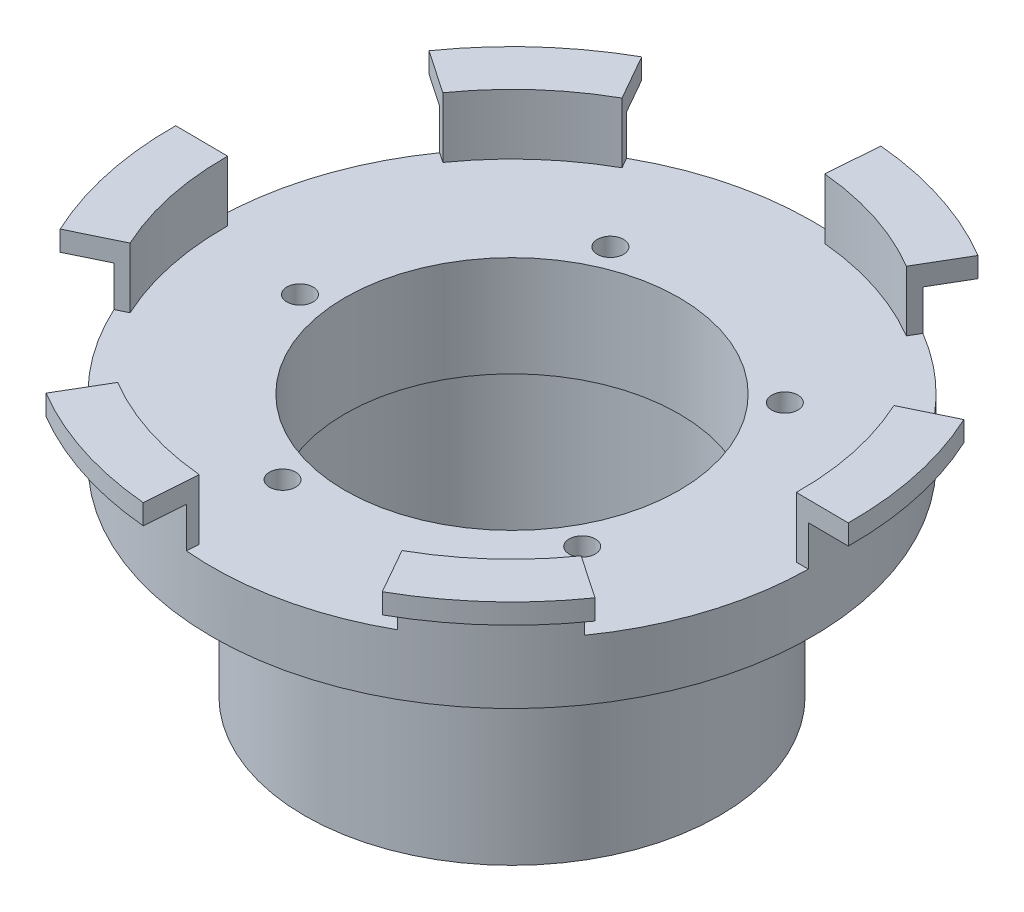
SolidWorks part; units mm, degrees
material "ABS PC"
ref_plane "Front Plane" through (0, 0, 0) normal (0, 0, 1) x (1, 0, 0)
ref_plane "Top Plane" through (0, 0, 0) normal (0, 1, 0) x (1, 0, 0)
ref_plane "Right Plane" through (0, 0, 0) normal (1, 0, 0) x (0, 0, -1)
sketch "Sketch1" plane through (0, 0, 0) normal (0, 1, 0) x (1, 0, 0)
  circle A0 centre (-1.3362, 19.9052) radius 41.5
  circle A1 centre (-1.3362, 19.9052) radius 71.5
  circle A2 centre (40.1859, -4.1762) radius 3.25
  circle A3 centre (34.3976, 51.9535) radius 3.25
  circle A4 centre (-20.7736, 63.7936) radius 3.25
  circle A5 centre (-49.083, 14.9815) radius 3.25
  circle A6 centre (-11.408, -27.0262) radius 3.25
  circle A7 centre (-1.3362, 19.9052) radius 41.5 construction
  dimension "D1" = 6.5
  dimension "D2" = 30
extrude "Boss-Extrude1" add sketch "Sketch1" along normal blind 15
sketch "Sketch3" plane through (0, 0, 0) normal (0, -1, 0) x (1, 0, 0)
  circle A0 centre (-1.3362, -19.9052) radius 71.5 construction
  circle A1 centre (-1.3362, -19.9052) radius 71.5
  circle A2 centre (-1.3362, -19.9052) radius 74.5
  dimension "D1" = 3
extrude "Boss-Extrude2" add sketch "Sketch3" against normal blind 30
sketch "Sketch4" plane through (0, 30, 0) normal (0, 1, 0) x (1, 0, 0)
  circle A0 centre (-1.3362, 19.9052) radius 74.5 construction
  circle A1 centre (-1.3362, 19.9052) radius 74.5
  circle A2 centre (-1.3362, 19.9052) radius 84.5
  dimension "D1" = 10
extrude "Boss-Extrude3" add sketch "Sketch4" against normal blind 5
sketch "Sketch5" plane through (0, 0, 0) normal (0, -1, 0) x (1, 0, 0)
  circle A0 centre (-1.3362, -19.9052) radius 41.5 construction
  circle A1 centre (-1.3362, -19.9052) radius 41.5
  circle A2 centre (-1.3362, -19.9052) radius 51.5
  dimension "D1" = 10
extrude "Boss-Extrude4" add sketch "Sketch5" along normal blind 50
sketch "Sketch6" plane through (0, -50, 0) normal (0, -1, 0) x (1, 0, 0)
  circle A0 centre (-1.3362, -19.9052) radius 41.5 construction
  circle A1 centre (-1.3362, -19.9052) radius 41.5
  circle A2 centre (-1.3362, -19.9052) radius 44.5
  dimension "D1" = 3
extrude "Cut-Extrude1" cut sketch "Sketch6" against normal blind 40
sketch "Sketch7" plane through (0, 30, 0) normal (0, 1, 0) x (1, 0, 0)
  line L0 (19.9502, 55.5302) -> (41.7368, 92.603)
  line L1 (36.552, 36.8385) -> (75.2869, 55.5302)
  circle A0 centre (-1.3362, 19.9052) radius 41.5 construction
  circle A1 centre (-1.3362, 19.9052) radius 84.5 construction
  arc A2 (75.2869, 55.5302) -> (41.7368, 92.603) centre (-1.3362, 19.9052) ccw
  arc A3 (36.552, 36.8385) -> (19.9502, 55.5302) centre (-1.3362, 19.9052) ccw
  dimension "D1" = 25
  dimension "D2" = 50
extrude "Cut-Extrude3" cut sketch "Sketch7" against normal up to surface (15 mm away) up to face at (-49.083, 15, -11.7315)
pattern_circular "CirPattern1" count 6 over 360 about axis through (-1.3362, 0, -19.9052) along (0, 1, 0) of "Cut-Extrude3"
